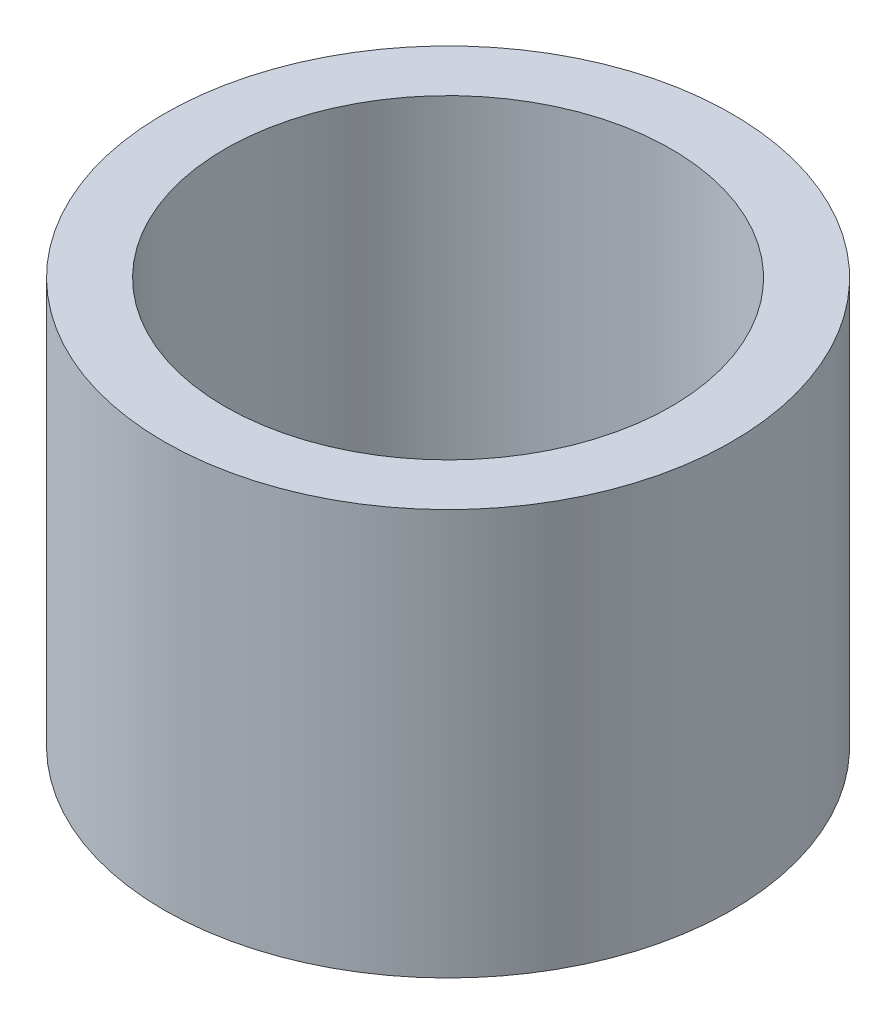
SolidWorks part; units mm, degrees
ref_plane "Front Plane" through (0, 0, 0) normal (0, 0, 1) x (1, 0, 0)
ref_plane "Top Plane" through (0, 0, 0) normal (0, 1, 0) x (1, 0, 0)
ref_plane "Right Plane" through (0, 0, 0) normal (1, 0, 0) x (0, 0, -1)
sketch "Sketch1" plane through (0, 0, 0) normal (0, 1, 0) x (1, 0, 0)
  circle A0 centre (0, 0) radius 7
  circle A1 centre (0, 0) radius 5.5
  dimension "D1" = 14
  dimension "D2" = 11
extrude "Boss-Extrude1" add sketch "Sketch1" along normal blind 10
